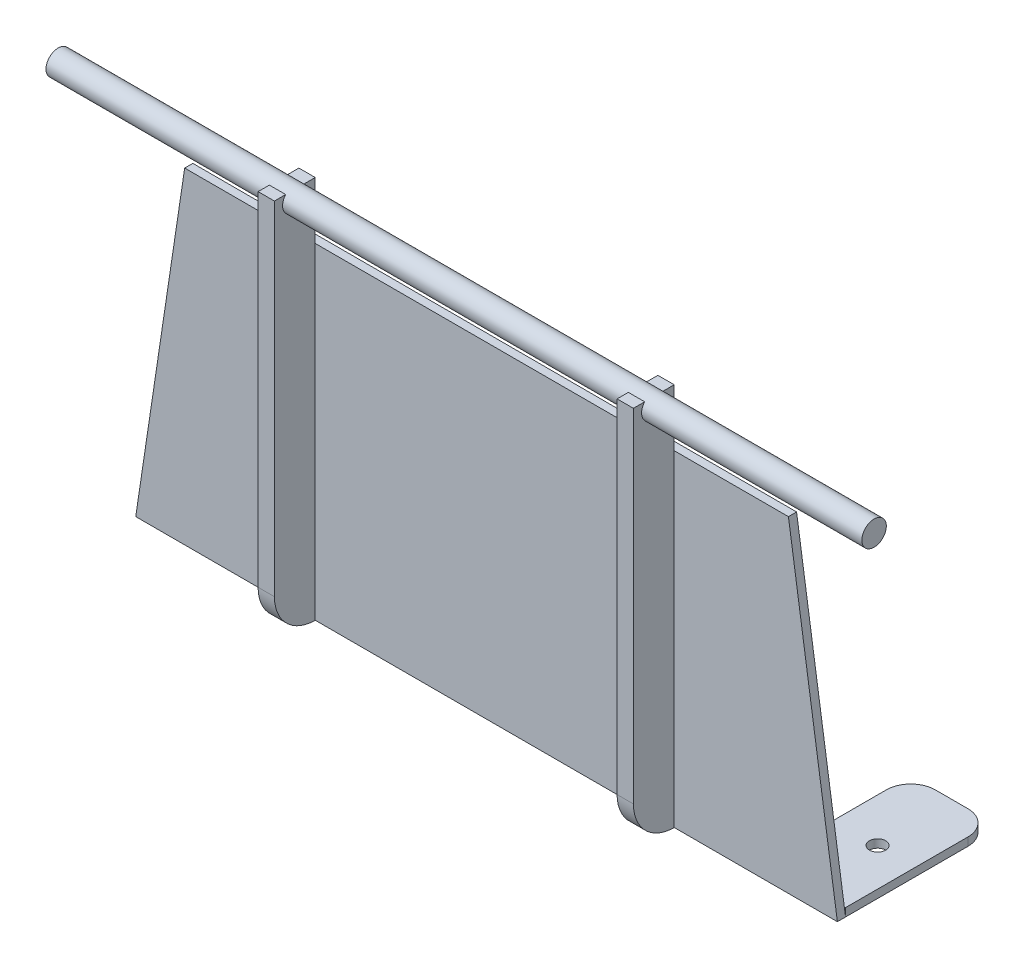
SolidWorks part; units mm, degrees
ref_plane "Front Plane" through (0, 0, 0) normal (0, 0, 1) x (1, 0, 0)
ref_plane "Top Plane" through (0, 0, 0) normal (0, 1, 0) x (1, 0, 0)
ref_plane "Right Plane" through (0, 0, 0) normal (1, 0, 0) x (0, 0, -1)
sketch "Sketch1" plane through (0, 0, 0) normal (0, 0, 1) x (1, 0, 0)
  line L0 (-43, 0) -> (43, 0)
  line L1 (43, 0) -> (43, 40) construction
  line L2 (43, 40) -> (37, 40) construction
  line L3 (37, 40) -> (-37, 40)
  line L4 (0, 40) -> (0, 0) construction
  line L5 (37, 40) -> (43, 0)
  line L6 (-37, 40) -> (-43, 0)
  point P2 (0, 0)
  dimension "D1" = 40
  dimension "D2" = 86
  dimension "D4" = 37
extrude "Boss-Extrude2" add sketch "Sketch1" along normal blind 1
ref_plane "Plane1" through (21, 0, 0) normal (1, 0, 0) x (0, 0, -1)
sketch "Sketch2" plane through (21, 0, 0) normal (1, 0, 0) x (0, 0, -1)
  line L2 (-1, 47) -> (-6, 47)
  line L5 (-1, 47) -> (-1, 0)
  line L6 (-1, 0) -> (-6, 0)
  line L7 (-6, 0) -> (-6, 47)
  dimension "D1" = 5
  dimension "D2" = 47
extrude "Boss-Extrude3" add sketch "Sketch2" along normal blind 2
fillet "Fillet2" radius 5 1 edges at (22, 0, 6)
mirror "Mirror2" about plane through (0, 0, 0) normal (1, 0, 0) of "Fillet2", "Boss-Extrude3"
ref_plane "Plane2" through (0, 46, 0) normal (0, 1, 0) x (1, 0, 0)
ref_plane "Plane3" through (50, 0, 0) normal (1, 0, 0) x (0, 0, -1)
sketch "Sketch3" plane through (50, 0, 0) normal (1, 0, 0) x (0, 0, -1)
  line L0 (-1, 47) -> (-6, 47) construction
  line L1 (-1, 47) -> (-6, 47) construction
  line L2 (12.7953, 46) -> (-12.7953, 46) construction
  circle A0 centre (-3.5, 46) radius 1.5
  point P2 (-3.5, 46)
  point P6 (-3.5, 47)
  dimension "D1" = 3
extrude "Boss-Extrude5" add sketch "Sketch3" against normal blind 100 contours A0
sketch "Sketch5" plane through (0, 0, 0) normal (0, 1, 0) x (1, 0, 0)
  line L0 (-43, 0) -> (-43, 18)
  line L1 (-43, 18) -> (-33, 18)
  line L2 (-33, 18) -> (-33, 0)
  line L3 (-43, 0) -> (43, 0) construction
  line L4 (-33, 0) -> (-43, 0)
  dimension "D1" = 18
  dimension "D2" = 10
extrude "Boss-Extrude6" add sketch "Sketch5" along normal blind 1
fillet "Fillet3" radius 3 2 edges at (-33, 0.5, -18) (-43, 0.5, -18)
sketch "Sketch6" plane through (0, 1, 0) normal (0, 1, 0) x (1, 0, 0)
  line L0 (-42.85, 0) -> (-33.8787, 17.1213) construction
  arc A0 (-33, 15) -> (-36, 18) centre (-36, 15) ccw construction
  circle A1 centre (-38.3643, 8.5607) radius 1
  point P9 (-38.3643, 8.5607)
  dimension "D1" = 2
extrude "Cut-Extrude1" cut sketch "Sketch6" against normal blind 1
mirror "Mirror4" about plane through (0, 0, 0) normal (1, 0, 0) of "Fillet3", "Cut-Extrude1", "Boss-Extrude6"
